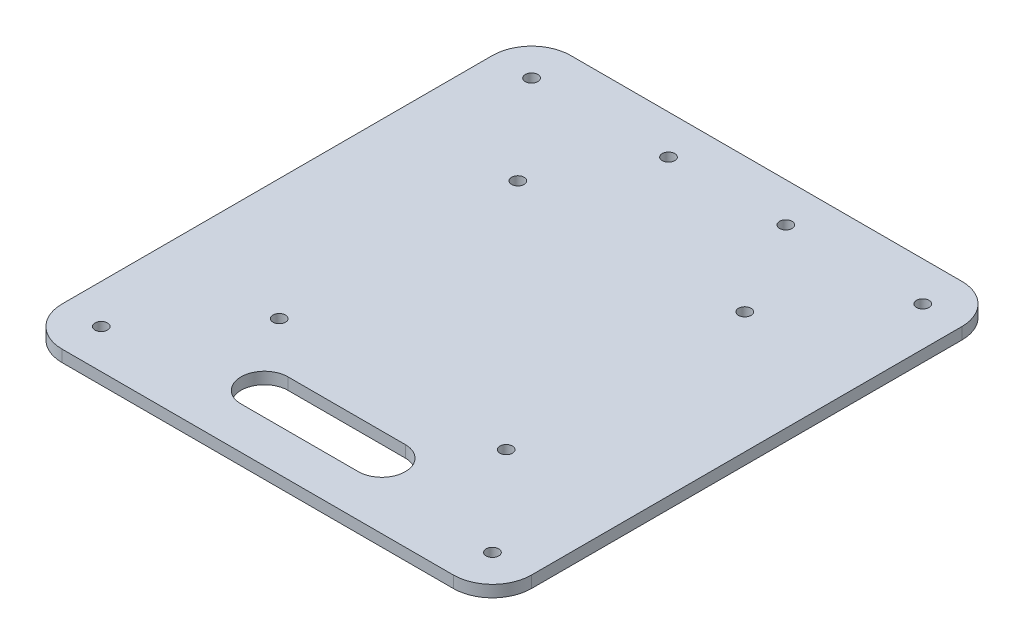
SolidWorks part; units mm, degrees
ref_plane "Front Plane" through (0, 0, 0) normal (0, 0, 1) x (1, 0, 0)
ref_plane "Top Plane" through (0, 0, 0) normal (0, 1, 0) x (1, 0, 0)
ref_plane "Right Plane" through (0, 0, 0) normal (1, 0, 0) x (0, 0, -1)
sketch "Sketch1" plane through (0, 0, 0) normal (0, 1, 0) x (1, 0, 0)
  line L0 (25.2381, 0) -> (225.0216, 0) construction
  line L1 (-50, 65) -> (50, 65)
  line L2 (-60, 55) -> (-60, -55)
  line L3 (-50, -65) -> (50, -65)
  line L4 (60, 55) -> (60, -55)
  line L5 (-60, 65) -> (60, -65) construction
  line L6 (-60, -65) -> (60, 65) construction
  line L7 (0, 0) -> (0, 90) construction
  line L8 (-15, -48.268) -> (15, -48.268) construction
  line L9 (-15, -42.268) -> (15, -42.268)
  line L10 (-15, -54.268) -> (15, -54.268)
  arc A0 (-60, -55) -> (-50, -65) centre (-50, -55) ccw
  arc A1 (50, -65) -> (60, -55) centre (50, -55) ccw
  arc A2 (50, 65) -> (60, 55) centre (50, 55) cw
  arc A3 (-50, 65) -> (-60, 55) centre (-50, 55) ccw
  circle A6 centre (50, -55) radius 1.6
  circle A8 centre (50, 55) radius 1.6
  circle A9 centre (-50, -55) radius 1.6
  circle A10 centre (-50, 55) radius 1.6
  arc A11 (-15, -42.268) -> (-15, -54.268) centre (-15, -48.268) ccw
  arc A12 (15, -54.268) -> (15, -42.268) centre (15, -48.268) ccw
  point P0 (0, -0.268)
  point P24 (0, -48.268)
  dimension "D3" = 48
  dimension "D1" = 30
  dimension "D2" = 12
extrude "Boss-Extrude1" add sketch "Sketch1" along normal blind 3
sketch "Sketch2" plane through (0, 0, 0) normal (0, 1, 0) x (1, 0, 0)
  line L0 (0, 0) -> (71.4457, 0) construction
  line L1 (0, 0) -> (0, 33.0736) construction
  line L3 (-29, 30.5) -> (29, 30.5) construction
  line L4 (-29, 30.5) -> (-29, -30.5) construction
  line L5 (-29, -30.5) -> (29, -30.5) construction
  line L6 (29, 30.5) -> (29, -30.5) construction
  line L7 (-29, 30.5) -> (29, -30.5) construction
  line L8 (-29, -30.5) -> (29, 30.5) construction
  circle A0 centre (29, 30.5) radius 1.6
  circle A1 centre (-29, 30.5) radius 1.6
  circle A2 centre (29, -30.5) radius 1.6
  circle A3 centre (-29, -30.5) radius 1.6
  point P4 (0, 0)
  dimension "D1" = 58
  dimension "D2" = 61
extrude "Cut-Extrude1" cut sketch "Sketch2" along normal blind 45
sketch "Sketch3" plane through (0, 3, 0) normal (0, 1, 0) x (1, 0, 0)
  line L0 (0, 7.5689) -> (0, 38.0786) construction
  circle A0 centre (-15, 55) radius 1.6
  circle A1 centre (15, 55) radius 1.6
  point P9 (65.8053, 41.1069)
  dimension "D1" = 15
  dimension "D2" = 15
  dimension "D3" = 55
extrude "Cut-Extrude2" cut sketch "Sketch3" against normal through all
